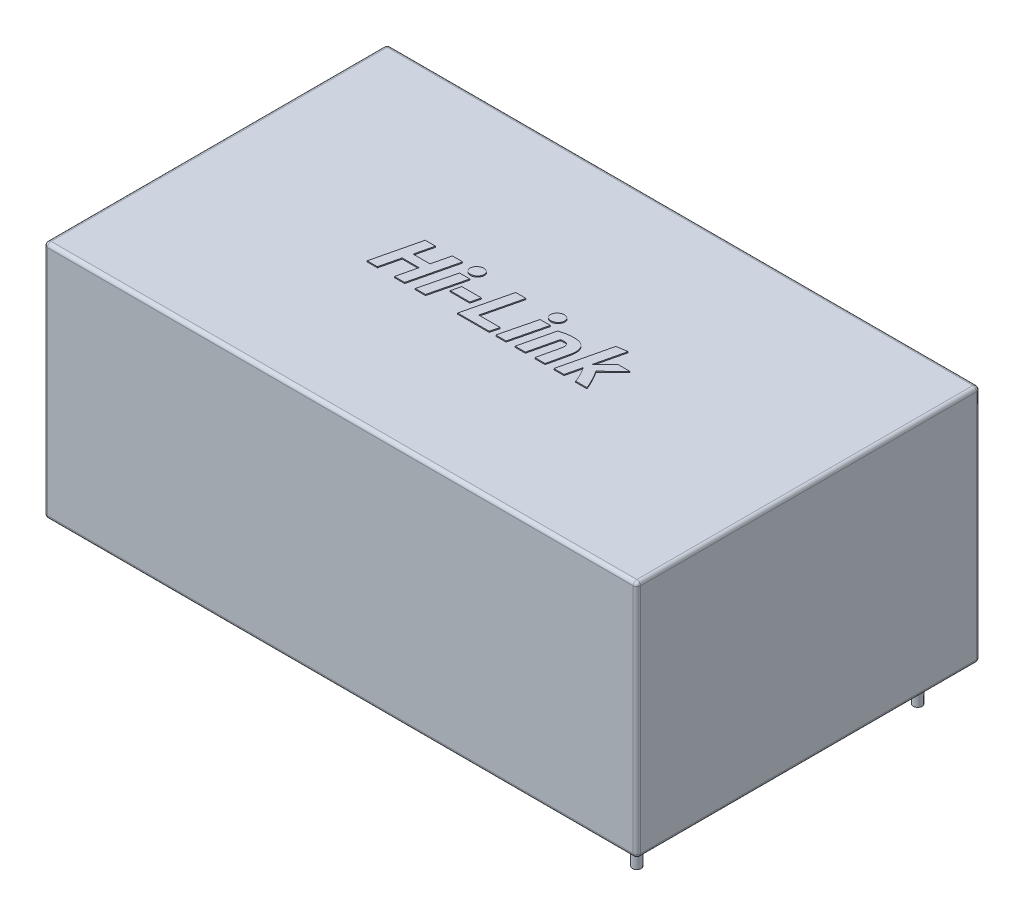
SolidWorks part; units mm, degrees
ref_plane "Front Plane" through (0, 0, 0) normal (0, 0, 1) x (1, 0, 0)
ref_plane "Top Plane" through (0, 0, 0) normal (0, 1, 0) x (1, 0, 0)
ref_plane "Right Plane" through (0, 0, 0) normal (1, 0, 0) x (0, 0, -1)
sketch "Sketch1" plane through (0, 0, 0) normal (0, 1, 0) x (1, 0, 0)
  line L1 (0, 0) -> (57, 0)
  line L2 (0, 0) -> (0, 33)
  line L3 (0, 33) -> (57, 33)
  line L4 (57, 0) -> (57, 33)
  dimension "D1" = 33
  dimension "D2" = 57
extrude "Boss-Extrude2" add sketch "Sketch1" along normal blind 23
sketch "Sketch2" plane through (0, 0, 0) normal (0, -1, 0) x (1, 0, 0)
  line L0 (0, -33) -> (0, 0) construction
  line L1 (0, 0) -> (57, 0) construction
  line L2 (57, 0) -> (57, -33) construction
  circle A0 centre (3, -12) radius 0.4233
  circle A1 centre (3, -21) radius 0.4233
  circle A2 centre (54, -30) radius 0.4233
  circle A3 centre (54, -3) radius 0.4233
  dimension "D3" = 0.8467
  dimension "D4" = 0.8467
  dimension "D7" = 0.8467
  dimension "D8" = 0.8467
  dimension "D1" = 3
  dimension "D2" = 12
  dimension "D5" = 9
  dimension "D6" = 27
  dimension "D9" = 3
  dimension "D10" = 3
extrude "Boss-Extrude3" add sketch "Sketch2" along normal blind 3.5
sketch "Sketch3" plane through (0, 23, 0) normal (0, 1, 0) x (1, 0, 0)
  text T0 "Hi-Link" font "Ubuntu" height 4.5
extrude "Boss-Extrude4" add sketch "Sketch3" along normal blind 0.1
fillet "Fillet1" radius 0.35 12 edges at (57, 11.5, -33) (57, 0, -16.5) (28.5, 0, -33) (0, 0, -16.5) (0, 11.5, -33) (28.5, 0, 0) (28.5, 23, -33) (57, 11.5, 0) (57, 23, -16.5) (0, 23, -16.5) (0, 11.5, 0) (28.5, 23, 0)
